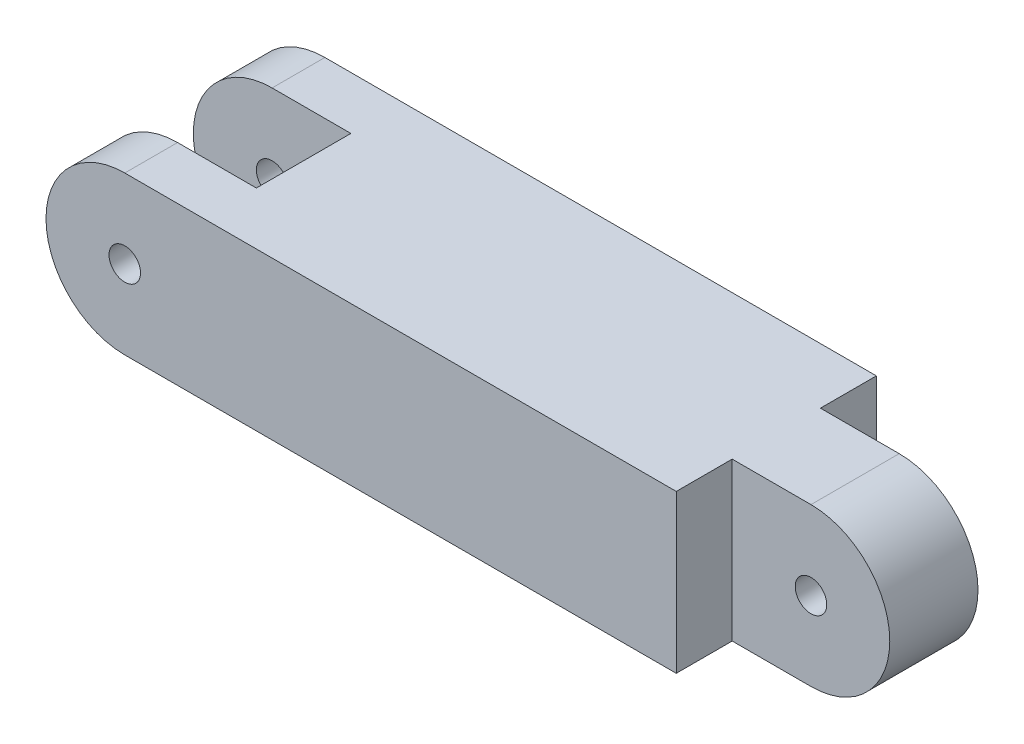
SolidWorks part; units mm, degrees
ref_plane "Front Plane" through (0, 0, 0) normal (0, 0, 1) x (1, 0, 0)
ref_plane "Top Plane" through (0, 0, 0) normal (0, 1, 0) x (1, 0, 0)
ref_plane "Right Plane" through (0, 0, 0) normal (1, 0, 0) x (0, 0, -1)
sketch "Sketch1" plane through (0, 0, 0) normal (0, 0, 1) x (1, 0, 0)
  line L0 (0, 0) -> (40, 0) construction
  line L1 (0, 5) -> (40, 5)
  line L2 (0, -5) -> (40, -5)
  arc A0 (0, 5) -> (0, -5) centre (0, 0) ccw
  arc A1 (40, -5) -> (40, 5) centre (40, 0) ccw
  point P3 (20, 0)
  dimension "D1" = 5
  dimension "D2" = 40
extrude "Boss-Extrude1" add sketch "Sketch1" along normal mid plane 12.7
sketch "Sketch2" plane through (0, 0, 6.35) normal (0, 0, 1) x (1, 0, 0)
  circle A0 centre (40, 0) radius 1
  arc A1 (40, -5) -> (40, 5) centre (40, 0) ccw construction
  circle A2 centre (0, 0) radius 1
  dimension "D1" = 2
  dimension "D2" = 2
extrude "Cut-Extrude1" cut sketch "Sketch2" against normal up to surface (12.7 mm away) up to face at (20, 0, -6.35)
sketch "Sketch3" plane through (0, 0, 6.35) normal (0, 0, 1) x (1, 0, 0)
  line L0 (35, 5) -> (35, -5)
  line L1 (40, 5) -> (0, 5) construction
  line L2 (0, -5) -> (40, -5) construction
  line L3 (35, -5) -> (40, -5)
  line L4 (40, 5) -> (35, 5)
  arc A3 (40, -5) -> (40, 5) centre (40, 0) ccw
  arc A4 (40, -5) -> (40, 5) centre (40, 0) ccw construction
extrude "Cut-Extrude2" cut sketch "Sketch3" against normal offset from surface (3.55 mm away) 2.8 up to plane "Front Plane"
mirror "Mirror1" about plane through (0, 0, 0) normal (0, 0, 1) of "Cut-Extrude2"
sketch "Sketch4" plane through (0, 0, 6.35) normal (0, 0, 1) x (1, 0, 0)
  line L0 (5, 5) -> (5, -5)
  line L1 (35, 5) -> (0, 5) construction
  line L2 (0, -5) -> (35, -5) construction
  line L3 (0, -5) -> (5, -5)
  line L4 (5, 5) -> (0, 5)
  arc A0 (0, 5) -> (0, -5) centre (0, 0) ccw
  arc A1 (0, 5) -> (0, -5) centre (0, 0) ccw construction
extrude "Cut-Extrude3" cut sketch "Sketch4" against normal mid plane 6 from surface at -6.35 starting at plane "Front Plane"
equation "\"LENGTH\"= 40"
equation "\"D2@Sketch1\"=\"LENGTH\""
